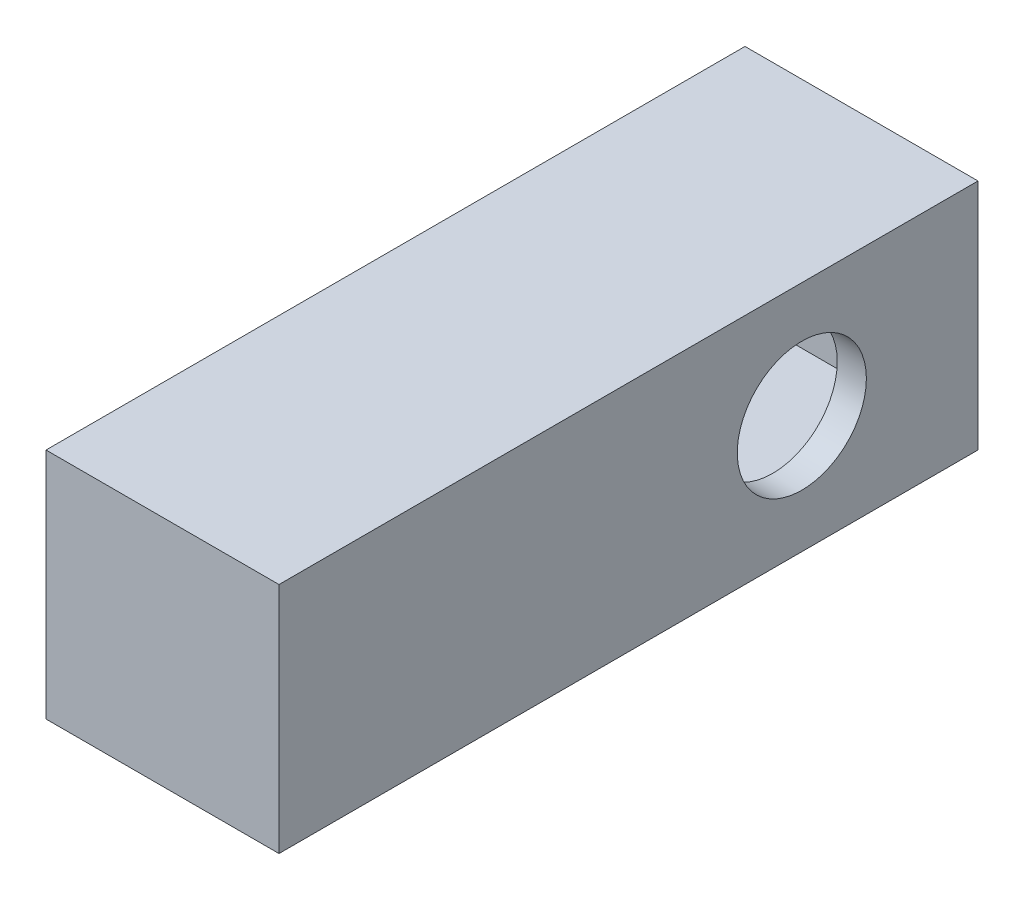
SolidWorks part; units mm, degrees
ref_plane "Front Plane" through (0, 0, 0) normal (0, 0, 1) x (1, 0, 0)
ref_plane "Top Plane" through (0, 0, 0) normal (0, 1, 0) x (1, 0, 0)
ref_plane "Right Plane" through (0, 0, 0) normal (1, 0, 0) x (0, 0, -1)
sketch "Sketch1" plane through (0, 0, 0) normal (0, 1, 0) x (1, 0, 0)
  line L1 (0, 0) -> (50.8, 0)
  line L2 (0, 0) -> (0, 152.4)
  line L3 (0, 152.4) -> (50.8, 152.4)
  line L4 (50.8, 0) -> (50.8, 152.4)
  dimension "D1" = 50.8
  dimension "D2" = 152.4
extrude "Boss-Extrude1" add sketch "Sketch1" along normal blind 50.8
shell "Shell1" thickness 6.35
sketch "Sketch4" plane through (50.8, 0, 0) normal (1, 0, 0) x (0, 0, -1)
  line L0 (152.4, 50.8) -> (152.4, 0) construction
  line L1 (0, 50.8) -> (152.4, 50.8) construction
  circle A0 centre (113.988, 25.6835) radius 14.075
  dimension "D1" = 28.15
  dimension "D2" = 38.412
  dimension "D3" = 25.1165
extrude "Cut-Extrude1" cut sketch "Sketch4" against normal blind 25
